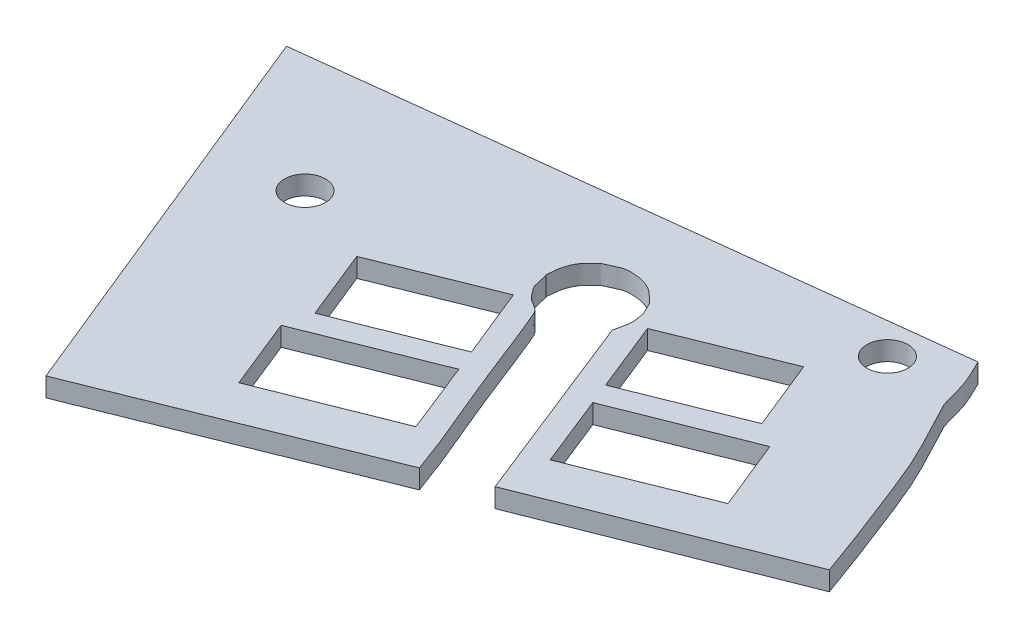
SolidWorks part; units mm, degrees
ref_plane "Front Plane" through (0, 0, 0) normal (0, 0, 1) x (1, 0, 0)
ref_plane "Top Plane" through (0, 0, 0) normal (0, 1, 0) x (1, 0, 0)
ref_plane "Right Plane" through (0, 0, 0) normal (1, 0, 0) x (0, 0, -1)
sketch "Sketch1" plane through (0, 0, 0) normal (0, 1, 0) x (1, 0, 0)
  line L0 (6.1521, 12.0078) -> (30.7603, 12.0078) construction
  line L1 (-3.9482, 25.8578) -> (34.7084, 30.3726)
  line L2 (41.3065, 14.4944) -> (26.3793, 8.5562)
  line L3 (26.3793, 8.5562) -> (21.5711, 20.6728)
  line L4 (22.9999, 7.2071) -> (6.3717, 0.5247)
  line L5 (6.3717, 0.5247) -> (-3.9482, 25.8578)
  line L6 (29.528, 24.668) -> (31.2954, 20.2924)
  line L11 (31.2954, 20.2924) -> (24.3349, 17.4974)
  line L12 (24.3349, 17.4974) -> (22.5827, 21.866)
  line L13 (22.5827, 21.866) -> (29.528, 24.668)
  line L14 (16.5778, 19.4932) -> (18.3623, 15.098)
  line L19 (18.3623, 15.098) -> (11.3765, 12.3133)
  line L20 (11.3765, 12.3133) -> (9.6115, 16.6866)
  line L21 (9.6115, 16.6866) -> (16.5778, 19.4932)
  line L22 (32.7866, 19.2988) -> (34.5598, 14.9094)
  line L23 (34.5598, 14.9094) -> (26.6479, 11.7224)
  line L24 (26.6479, 11.7224) -> (24.8826, 16.1536)
  line L25 (24.8826, 16.1536) -> (32.7866, 19.2988)
  line L26 (18.8984, 13.7726) -> (20.6613, 9.3244)
  line L27 (20.6613, 9.3244) -> (12.7599, 6.178)
  line L28 (12.7599, 6.178) -> (10.9743, 10.6019)
  line L29 (10.9743, 10.6019) -> (18.8984, 13.7726)
  circle A0 centre (31.582, 27.844) radius 1.2816
  circle A1 centre (4.4439, 18.6222) radius 1.2791
  spline S0 degree 3 poles (34.7084, 30.3726) (34.9423, 29.8626) (35.2165, 29.3692) (35.41, 28.8426) (35.6349, 28.2308) (35.7689, 27.5892) (35.9606, 26.9662) (35.9659, 26.9489) (35.9911, 26.9442) (35.9993, 26.9281) (36.7439, 25.465) (37.5642, 24.0369) (38.2178, 22.5309) (38.8653, 21.0391) (40.4414, 16.9604) (41.3065, 14.4944) knots 0 0 0 0 1 1 1 2 2 2 3 3 3 4 4 4 5 5 5 5
  spline S1 degree 3 poles (21.5711, 20.6728) (21.6349, 21.0182) (21.7486, 21.358) (21.7624, 21.7089) (21.7742, 22.0053) (21.6958, 22.2987) (21.6469, 22.5913) (21.6439, 22.6091) (21.6175, 22.614) (21.6085, 22.6296) (21.4549, 22.8982) (21.3835, 23.2349) (21.1477, 23.4352) (20.9055, 23.6408) (20.6926, 23.8883) (20.4183, 24.0487) (20.1599, 24.1998) (19.8708, 24.3154) (19.5741, 24.3552) (19.1803, 24.408) (18.7433, 24.4488) (18.3847, 24.2778) (18.1315, 24.1571) (17.8707, 24.0528) (17.6175, 23.9321) (17.6011, 23.9243) (17.5915, 23.9069) (17.5791, 23.8937) (17.3615, 23.6637) (17.1044, 23.4652) (16.9272, 23.2028) (16.7797, 22.9842) (16.6873, 22.7287) (16.6206, 22.4736) (16.5456, 22.1866) (16.5442, 21.8852) (16.506, 21.591) knots 0 0 0 0 1 1 1 2 2 2 3 3 3 4 4 4 5 5 5 6 6 6 7 7 7 8 8 8 9 9 9 10 10 10 11 11 11 12 12 12 12
  spline S2 degree 3 poles (16.506, 21.591) (16.5188, 21.5783) (16.5398, 21.5702) (16.5444, 21.5527) (16.6174, 21.2736) (16.6638, 20.9879) (16.7368, 20.7087) (16.8068, 20.441) (17.044, 20.2485) (17.1977, 20.0184) (17.4656, 19.6171) (18.0312, 19.5778) (18.2342, 19.0982) (19.1275, 16.9888) (19.3467, 16.3313) (20.0022, 14.687) (21.5189, 10.8821) (22.0115, 9.9866) (22.9999, 7.2071) knots 0 0 0 0 1 1 1 2 2 2 3 3 3 4 4 4 5 5 5 6 6 6 6
  dimension "D1" = 17.9207
extrude "Boss-Extrude1" add sketch "Sketch1" along normal blind 1.19
